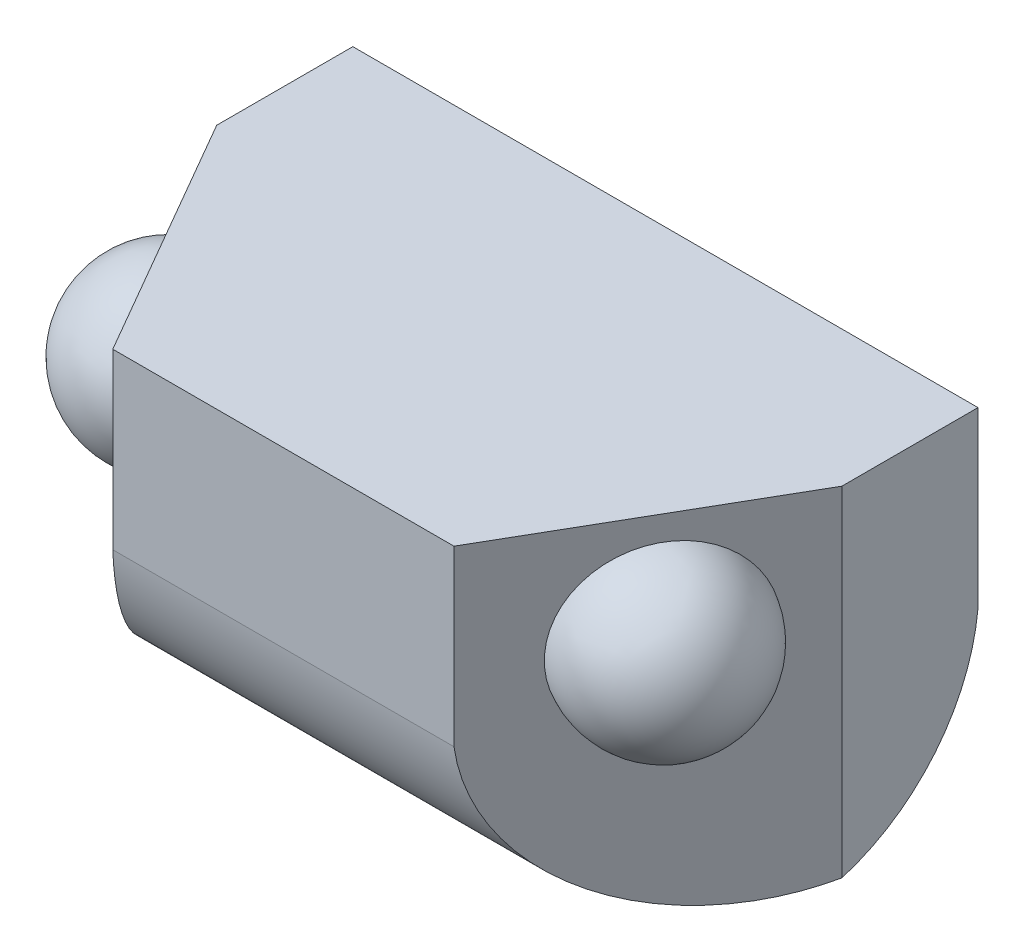
SolidWorks part; units mm, degrees
ref_plane "Front Plane" through (0, 0, 0) normal (0, 0, 1) x (1, 0, 0)
ref_plane "Top Plane" through (0, 0, 0) normal (0, 1, 0) x (1, 0, 0)
ref_plane "Right Plane" through (0, 0, 0) normal (1, 0, 0) x (0, 0, -1)
sketch "Sketch1" plane through (0, 0, 0) normal (0, 1, 0) x (1, 0, 0)
  line L1 (-90, -55) -> (90, -55)
  line L2 (-90, -55) -> (-90, 55)
  line L3 (-90, 55) -> (90, 55)
  line L4 (90, -55) -> (90, 55)
  line L5 (-90, -55) -> (90, 55) construction
  line L6 (-90, 55) -> (90, -55) construction
  point P0 (0, 0)
  dimension "D1" = 110
  dimension "D2" = 180
extrude "Boss-Extrude1" add sketch "Sketch1" along normal blind 50
sketch "Sketch2" plane through (-90, 0, 0) normal (-1, 0, 0) x (0, 0, 1)
  line L0 (-55, 0) -> (55, 0) construction
  line L1 (-55, 0) -> (55, 0)
  arc A0 (-55, 0) -> (55, 0) centre (0, 5.25) ccw
  point P3 (0, -50)
  dimension "D1" = 50
extrude "Boss-Extrude2" add sketch "Sketch2" against normal blind 180
sketch "Sketch3" plane through (0, 50, 0) normal (0, 1, 0) x (1, 0, 0)
  line L0 (-49.1188, -55) -> (-90, 15.8083)
  line L1 (-90, -55) -> (90, -55) construction
  line L2 (-90, 55) -> (-90, -55) construction
  line L3 (-90, 15.8083) -> (-90, -55)
  line L4 (-90, -55) -> (-49.1188, -55)
  dimension "D1" = 30
extrude "Cut-Extrude1" cut sketch "Sketch3" against normal through all
mirror "Mirror1" about plane through (0, 0, 0) normal (1, 0, 0) of "Cut-Extrude1"
sketch "Sketch4" plane through (-60.6548, 0, 35.0191) normal (-0.866, 0, 0.5) x (0.5, 0, 0.866)
  line L0 (-20.9652, 42.9426) -> (-20.9652, -7.0574)
  arc A1 (-20.9652, 42.9426) -> (-20.9652, -7.0574) centre (-20.9652, 17.9426) cw
  dimension "D1" = 50
sketch "Sketch5" plane through (0, 0, -55) normal (0, 0, -1) x (-1, 0, 0)
  circle A0 centre (0, 0) radius 5
  dimension "D1" = 0
extrude "Boss-Extrude5" add sketch "Sketch5" along normal blind 10 and the other way blind 10
revolve "Revolve1" add sketch "Sketch4" angle 360 about L0
mirror "Mirror2" about plane through (0, 0, 0) normal (1, 0, 0) of "Revolve1"
